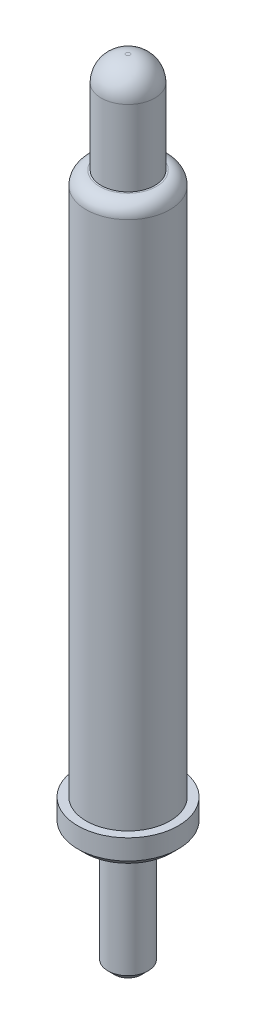
SolidWorks part; units mm, degrees
ref_plane "Спереди" through (0, 0, 0) normal (0, 0, 1) x (1, 0, 0)
ref_plane "Сверху" through (0, 0, 0) normal (0, 1, 0) x (1, 0, 0)
ref_plane "Справа" through (0, 0, 0) normal (1, 0, 0) x (0, 0, -1)
sketch "Эскиз1" plane through (0, 0, 0) normal (1, 0, 0) x (0, 0, -1)
  line L0 (0, 0) -> (0, 16.3551) construction
  line L1 (-0.2, 0) -> (-0.3, 0.1)
  line L2 (0, 0) -> (-0.2, 0)
  line L3 (0, 0) -> (0, 1.8)
  line L4 (0, 1.8) -> (-0.3, 1.8)
  line L5 (-0.3, 0.1) -> (-0.3, 1.8)
  line L6 (-0.65, 1.8) -> (-0.75, 1.9)
  line L7 (0, 1.8) -> (-0.65, 1.8)
  line L8 (0, 1.8) -> (0, 2.2)
  line L9 (0, 2.2) -> (-0.75, 2.2)
  line L10 (-0.75, 1.9) -> (-0.75, 2.2)
  line L12 (0, 2.2) -> (-0.625, 2.2)
  line L13 (0, 2.2) -> (0, 10.3)
  line L14 (0, 10.3) -> (-0.425, 10.3)
  line L15 (-0.625, 2.2) -> (-0.625, 10.1)
  line L16 (0, 10.3) -> (-0.4, 10.3)
  line L17 (0, 10.3) -> (0, 11.8)
  line L18 (0, 11.8) -> (-0.03, 11.8)
  line L19 (-0.4, 10.3) -> (-0.4, 11.43)
  arc A0 (-0.425, 10.3) -> (-0.625, 10.1) centre (-0.425, 10.1) ccw
  arc A1 (-0.03, 11.8) -> (-0.4, 11.43) centre (-0.03, 11.43) ccw
  point P5 (-0.3, 0)
  point P10 (-0.75, 1.8)
  dimension "D9" = 0.2
  dimension "D12" = 0.37
  dimension "D1" = 0.3
  dimension "D2" = 1.8
  dimension "D3" = 0.75
  dimension "D5" = 0.4
  dimension "D7" = 0.625
  dimension "D10" = 10
  dimension "D6" = 8.5
  dimension "D11" = 0.4
revolve "Повернуть1" add sketch "Эскиз1" angle 360 about L0
equation "\"D7@Эскиз1\"=1.25/2"
